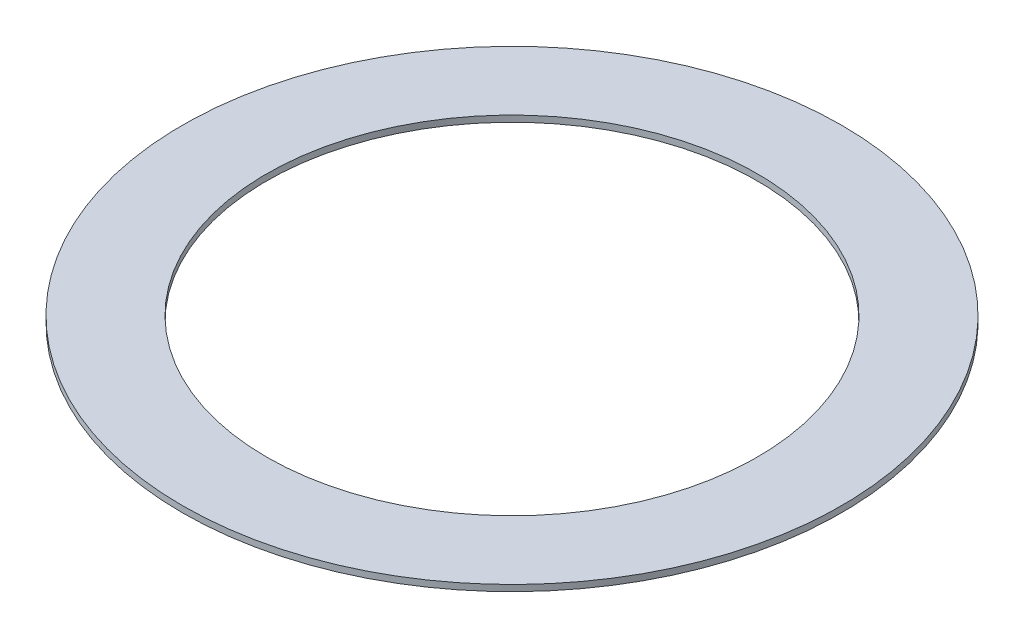
SolidWorks part; units mm, degrees
ref_plane "Front Plane" through (0, 0, 0) normal (0, 0, 1) x (1, 0, 0)
ref_plane "Top Plane" through (0, 0, 0) normal (0, 1, 0) x (1, 0, 0)
ref_plane "Right Plane" through (0, 0, 0) normal (1, 0, 0) x (0, 0, -1)
sketch "Sketch1" plane through (0, 0, 0) normal (0, 1, 0) x (1, 0, 0)
  circle A0 centre (0, 0) radius 158.6366
  circle A1 centre (0, 0) radius 118.121
extrude "Boss-Extrude1" add sketch "Sketch1" along normal blind 3
